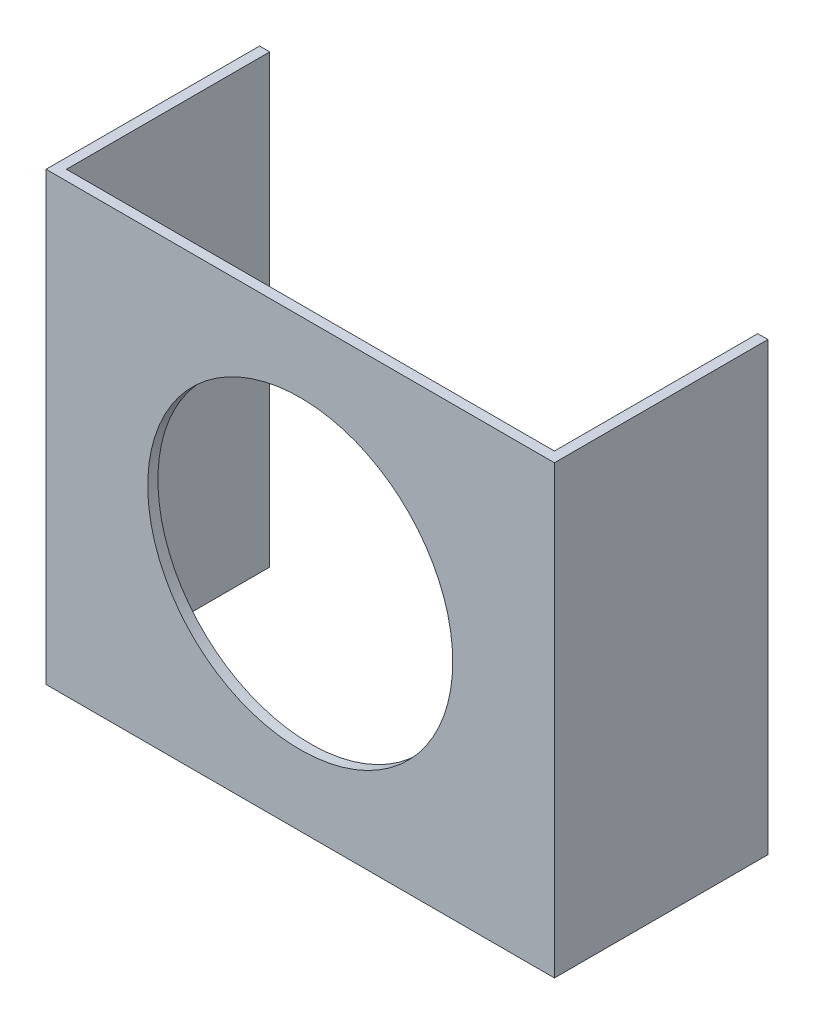
SolidWorks part; units mm, degrees
ref_plane "Front Plane" through (0, 0, 0) normal (0, 0, 1) x (1, 0, 0)
ref_plane "Top Plane" through (0, 0, 0) normal (0, 1, 0) x (1, 0, 0)
ref_plane "Right Plane" through (0, 0, 0) normal (1, 0, 0) x (0, 0, -1)
sketch "Sketch1" plane through (0, 0, 0) normal (0, 0, 1) x (1, 0, 0)
  line L0 (20, -16) -> (20, 16) construction
  line L1 (-25, 21.9442) -> (25, 21.9442)
  line L2 (-25, 21.9442) -> (-25, -21.9442)
  line L3 (-25, -21.9442) -> (25, -21.9442)
  line L4 (25, 21.9442) -> (25, -21.9442)
  line L5 (-25, 21.9442) -> (25, -21.9442) construction
  line L6 (-25, -21.9442) -> (25, 21.9442) construction
  point P0 (0, 0)
  dimension "D1" = 5
extrude "Boss-Extrude1" add sketch "Sketch1" along normal blind 1
sketch "Sketch2" plane through (0, 0, 0) normal (0, 0, -1) x (-1, 0, 0)
  line L0 (-25, 21.9442) -> (-25, -21.9442)
  line L2 (25, -21.9442) -> (-25, -21.9442) construction
  line L3 (-24, -21.9442) -> (-24, 21.9442)
  line L4 (-25, 21.9442) -> (25, 21.9442) construction
  line L7 (25, 21.9442) -> (25, -21.9442) construction
  line L8 (25, 21.0013) -> (25, 21.9442)
  line L9 (24, -21.9442) -> (25, -21.9442)
  line L10 (24, 21.9442) -> (24, -21.9442)
  line L11 (24, 21.9442) -> (25, 21.9442)
  line L12 (25, -21.9442) -> (25, 21.9442)
  line L13 (-25, 21.9442) -> (-24, 21.9442)
  line L15 (-25, -21.9442) -> (-24, -21.9442)
  line M12 (-25, -21.9442) -> (25, -21.9442)
  line M13 (25, -21.9442) -> (25, 21.9442)
  line M14 (25, 21.9442) -> (-25, 21.9442)
  dimension "D1" = 1
  dimension "D3" = 1
extrude "Boss-Extrude3" add sketch "Sketch2" along normal blind 20 contours L10 M14 M12 M13 | L0 L15 L3 L13
sketch "Sketch3" plane through (0, 0, 1) normal (0, 0, 1) x (1, 0, 0)
  circle A0 centre (0, 0) radius 15
  dimension "D1" = 30
extrude "Cut-Extrude1" cut sketch "Sketch3" against normal through all
